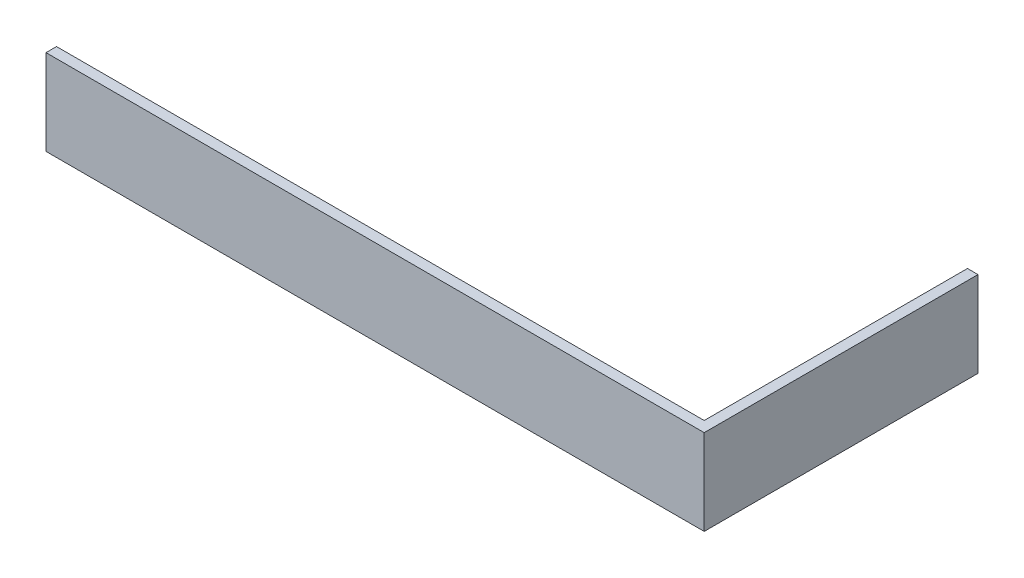
SolidWorks part; units mm, degrees
material "Custom Plastic"
ref_plane "X-Y Datum" through (0, 0, 0) normal (0, 0, 1) x (1, 0, 0)
ref_plane "X-Z Datum" through (0, 0, 0) normal (0, 1, 0) x (1, 0, 0)
ref_plane "Y-Z Datum" through (0, 0, 0) normal (1, 0, 0) x (0, 0, -1)
sketch "Sketch1" plane through (0, 0, 0) normal (0, 0, 1) x (1, 0, 0)
  line L1 (-50, -6.5) -> (50, -6.5)
  line L2 (-50, -6.5) -> (-50, 6.5)
  line L3 (-50, 6.5) -> (50, 6.5)
  line L4 (50, -6.5) -> (50, 6.5)
  line L5 (-50, -6.5) -> (50, 6.5) construction
  line L6 (-50, 6.5) -> (50, -6.5) construction
  point P0 (0, 0)
  dimension "D1" = 100
  dimension "D2" = 13
extrude "Boss-Extrude1" add sketch "Sketch1" along normal blind 1.6
sketch "Sketch3" plane through (0, 0, 0) normal (0, 0, -1) x (-1, 0, 0)
  line L0 (-50, 6.5) -> (50, 6.5) construction
  line L1 (-50, -6.5) -> (-48.4, -6.5)
  line L2 (-50, -6.5) -> (-50, 6.5)
  line L3 (-50, 6.5) -> (-48.4, 6.5)
  line L4 (-48.4, -6.5) -> (-48.4, 6.5)
  dimension "D1" = 1.6
extrude "Boss-Extrude2" add sketch "Sketch3" along normal blind 40
